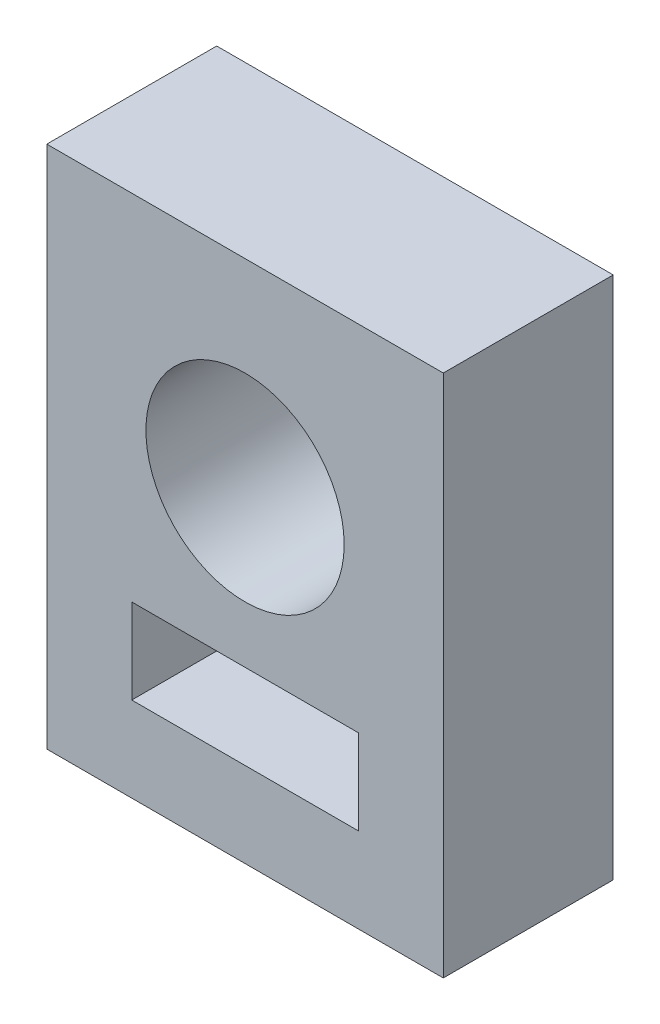
SolidWorks part; units mm, degrees
ref_plane "Front Plane" through (0, 0, 0) normal (0, 0, 1) x (1, 0, 0)
ref_plane "Top Plane" through (0, 0, 0) normal (0, 1, 0) x (1, 0, 0)
ref_plane "Right Plane" through (0, 0, 0) normal (1, 0, 0) x (0, 0, -1)
sketch "Sketch1" plane through (0, 0, 0) normal (0, 0, 1) x (1, 0, 0)
  line L5 (0, -1.25) -> (0, -3.25) construction
  line L7 (-7, -9.25) -> (7, -9.25)
  line L32 (-7, -9.25) -> (-7, 9.25)
  line L54 (-7, 9.25) -> (7, 9.25)
  line L59 (7, -9.25) -> (7, 9.25)
  line L60 (-7, -9.25) -> (7, 9.25) construction
  line L67 (-7, 9.25) -> (7, -9.25) construction
  line L76 (-4, -6.25) -> (4, -6.25)
  line L77 (-4, -6.25) -> (-4, -3.25)
  line L78 (-4, -3.25) -> (4, -3.25)
  line L79 (4, -6.25) -> (4, -3.25)
  line L80 (-4, -6.25) -> (4, -3.25) construction
  line L81 (-4, -3.25) -> (4, -6.25) construction
  circle A1 centre (0, 2.25) radius 3.5
  point P0 (0, 0)
  point P8 (0, -4.75)
  dimension "D3" = 7
  dimension "D2" = 3
  dimension "D4" = 7
  dimension "D5" = 2
  dimension "D10" = 7
  dimension "D6" = 8
  dimension "D7" = 3
  dimension "D8" = 3
  dimension "D9" = 3
  dimension "D11" = 14
  dimension "D12" = 18.5
extrude "Boss-Extrude1" add sketch "Sketch1" along normal blind 6
